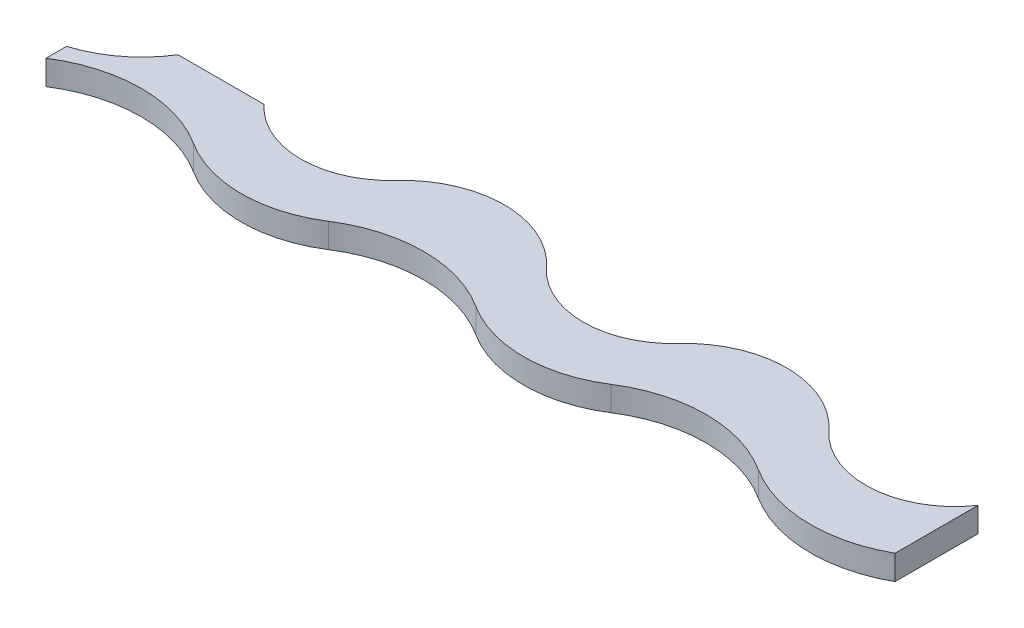
SolidWorks part; units mm, degrees
material "5052-H32"
ref_plane "Front Plane" through (0, 0, 0) normal (0, 0, 1) x (1, 0, 0)
ref_plane "Top Plane" through (0, 0, 0) normal (0, 1, 0) x (1, 0, 0)
ref_plane "Right Plane" through (0, 0, 0) normal (1, 0, 0) x (0, 0, -1)
sketch "Sketch2" plane through (0, 0, 0) normal (0, 1, 0) x (1, 0, 0)
  line L0 (63.347, 15.7747) -> (63.347, 9.0347)
  line L4 (-5.99, 9.3747) -> (-5.99, 11.0447)
  line L5 (6.1205, 14.9847) -> (-0.8676, 14.9847)
  arc A17 (5.99, 9.3747) -> (-5.99, 9.3747) centre (0, 0) ccw
  arc A18 (5.99, 9.3747) -> (16.96, 9.3747) centre (11.475, 17.9591) ccw
  arc A19 (16.96, 9.3747) -> (28.94, 9.3747) centre (22.95, 0) cw
  arc A20 (28.94, 9.3747) -> (39.91, 9.3747) centre (34.425, 17.9591) ccw
  arc A21 (39.91, 9.3747) -> (51.89, 9.3747) centre (45.9, 0) cw
  arc A22 (51.89, 9.3747) -> (63.347, 9.0347) centre (57.9028, 18.7851) ccw
  arc A23 (52.0205, 14.9847) -> (63.347, 15.7747) centre (57.37, 19.8782) ccw
  arc A24 (52.0205, 14.9847) -> (39.7695, 14.9847) centre (45.895, 9.3814) ccw
  arc A25 (39.7695, 14.9847) -> (29.0705, 14.9847) centre (34.42, 19.8782) cw
  arc A26 (29.0705, 14.9847) -> (16.8195, 14.9847) centre (22.945, 9.3814) ccw
  arc A27 (16.8195, 14.9847) -> (6.1205, 14.9847) centre (11.47, 19.8782) cw
  arc A28 (-0.8676, 14.9847) -> (-5.99, 11.0447) centre (-8.7131, 19.8848) cw
  circle A29 centre (0, 0) radius 10.875
  circle A31 centre (-8.7131, 19.8848) radius 9
  circle A32 centre (22.95, 0) radius 10.875
  circle A33 centre (45.9, 0) radius 10.875
  circle A34 centre (11.47, 19.8782) radius 7
  circle A35 centre (34.42, 19.8782) radius 7
  circle A36 centre (57.37, 19.8782) radius 7
  dimension "D1" = 21.75
  dimension "D2" = 11.125
  dimension "D3" = 9.25
  dimension "D6" = 1.67
  dimension "D9" = 22.95
  dimension "D11" = 14
  dimension "D12" = 22.95
  dimension "D4" = 18
  dimension "D8" = 22.95
  dimension "D10" = 7.25
  dimension "D5" = 5.99
  dimension "D7" = 21.71
  dimension "D13" = 22.95
  dimension "D14" = 22.95
  dimension "D15" = 11.47
  dimension "D16" = 3.94
  dimension "D17" = 6.74
  dimension "D18" = 0.34
extrude "Boss-Extrude1" add sketch "Sketch2" along normal blind 2 contours A24 A25 A26 A27 L5 A28 L4 A17 A18 A19 A20 A21 A22 L0 A23
